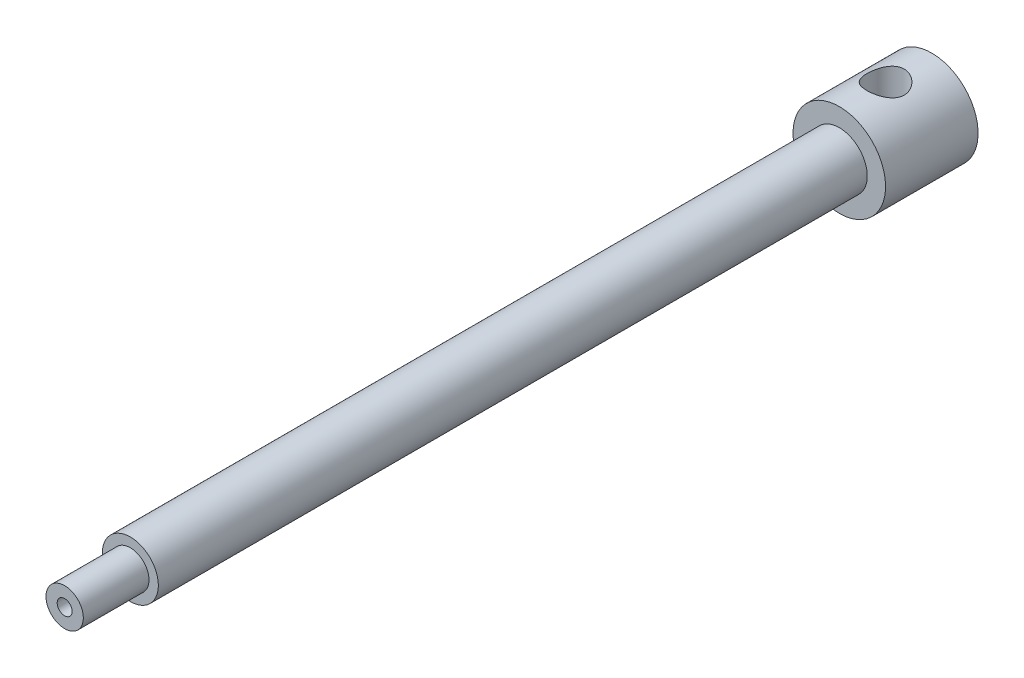
SolidWorks part; units mm, degrees
ref_plane "Front Plane" through (0, 0, 0) normal (0, 0, 1) x (1, 0, 0)
ref_plane "Top Plane" through (0, 0, 0) normal (0, 1, 0) x (1, 0, 0)
ref_plane "Right Plane" through (0, 0, 0) normal (1, 0, 0) x (0, 0, -1)
sketch "Sketch1" plane through (0, 0, 0) normal (0, 1, 0) x (1, 0, 0)
  line L0 (0, 59.311) -> (0, -69.7836) construction
  line L1 (0, 81.2702) -> (-7.874, 81.2702)
  line L2 (-7.874, 65.5222) -> (-4.7625, 65.5222)
  line L3 (-4.7625, 65.5222) -> (-4.7625, -55.1278)
  line L4 (-4.7625, -55.1278) -> (-3.175, -55.1278)
  line L5 (-3.175, -55.1278) -> (-3.175, -66.3038)
  line L8 (-7.874, 65.5222) -> (-7.874, 81.2702)
  line L9 (-3.175, -66.3038) -> (-1.27, -66.3038)
  line L10 (-1.27, -66.3038) -> (-1.27, -57.9421)
  line L11 (-1.27, -57.9421) -> (0, -57.9421)
  line L12 (0, -57.9421) -> (0, 81.2702)
  point P7 (0, -69.7836)
  dimension "D1" = 6.35
  dimension "D2" = 9.525
  dimension "D3" = 120.65
  dimension "D4" = 15.748
  dimension "D5" = 11.176
  dimension "D6" = 15.748
revolve "Revolve1" add sketch "Sketch1" angle 360 about L0
cosmetic thread "Cosmetic Thread1" parameters "D2"=8.2652
sketch "Sketch2" plane through (0, 0, 0) normal (0, 1, 0) x (1, 0, 0)
  line L0 (-7.874, 81.2702) -> (7.874, 81.2702) construction
  line L1 (7.874, 81.2702) -> (-7.874, 81.2702) construction
  line L2 (7.874, 81.2702) -> (-7.874, 65.5222) construction
  line L3 (-7.874, 65.5222) -> (7.874, 65.5222) construction
  line L4 (-7.874, 65.5222) -> (7.874, 65.5222) construction
  line L5 (7.874, 65.5222) -> (-7.874, 81.2702) construction
  circle A0 centre (0, 73.3962) radius 3.175
  dimension "D1" = 6.35
extrude "Cut-Extrude1" cut sketch "Sketch2" against normal through all both and the other way through all contours A0
